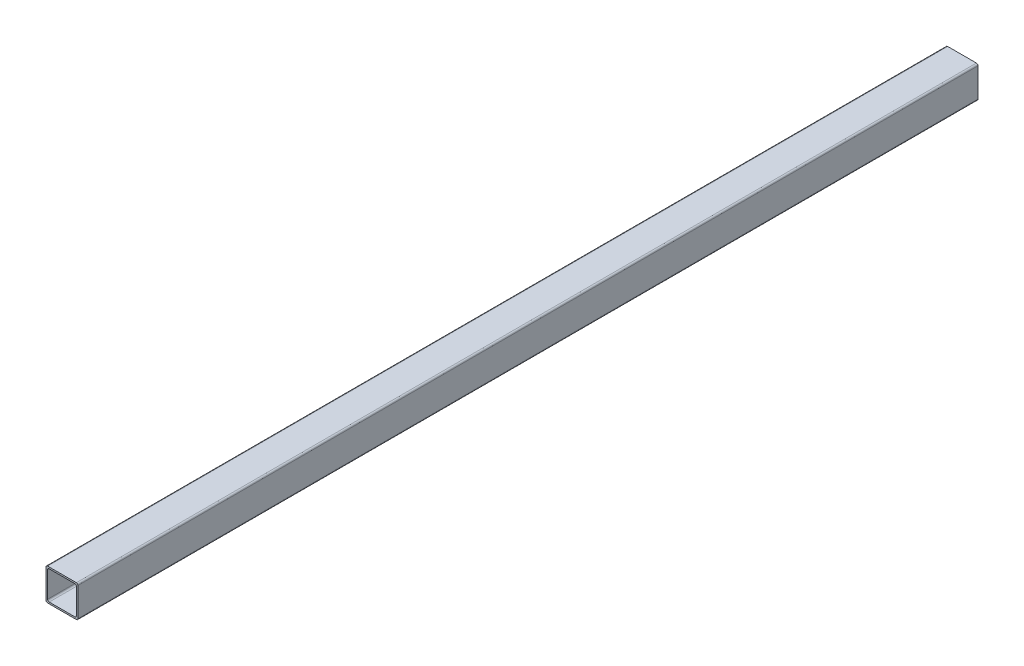
SolidWorks part; units mm, degrees
ref_plane "Płaszczyzna przednia" through (0, 0, 0) normal (0, 0, 1) x (1, 0, 0)
ref_plane "Płaszczyzna górna" through (0, 0, 0) normal (0, 1, 0) x (1, 0, 0)
ref_plane "Płaszczyzna prawa" through (0, 0, 0) normal (1, 0, 0) x (0, 0, -1)
sketch "Szkic1" plane through (0, 0, 0) normal (0, 0, 1) x (1, 0, 0)
  line L0 (3, 6) -> (3, 54)
  line L1 (3, 0) -> (57, 0)
  line L2 (0, 3) -> (0, 57)
  line L3 (3, 60) -> (57, 60)
  line L4 (60, 3) -> (60, 57)
  line L5 (0, 0) -> (42.6554, 0)
  line L6 (0, 0) -> (0, 31.4913)
  line L7 (6, 57) -> (54, 57)
  line L8 (57, 6) -> (57, 54)
  line L9 (6, 3) -> (54, 3)
  arc A0 (57, 60) -> (60, 57) centre (57, 57) cw
  arc A1 (54, 57) -> (57, 54) centre (54, 54) cw
  arc A2 (57, 0) -> (60, 3) centre (57, 3) ccw
  arc A3 (57, 6) -> (54, 3) centre (54, 6) cw
  arc A4 (3, 6) -> (6, 3) centre (6, 6) ccw
  arc A5 (3, 0) -> (0, 3) centre (3, 3) cw
  arc A6 (3, 54) -> (6, 57) centre (6, 54) cw
  arc A7 (0, 57) -> (3, 60) centre (3, 57) cw
  dimension "D1" = 3
extrude "Dodanie-wyciągnięcie1" add sketch "Szkic1" along normal blind 1690 contours A7 L2 A5 L1 A2 L4 A0 L3 L0 A6 L7 A1 L8 A3 L9 A4
